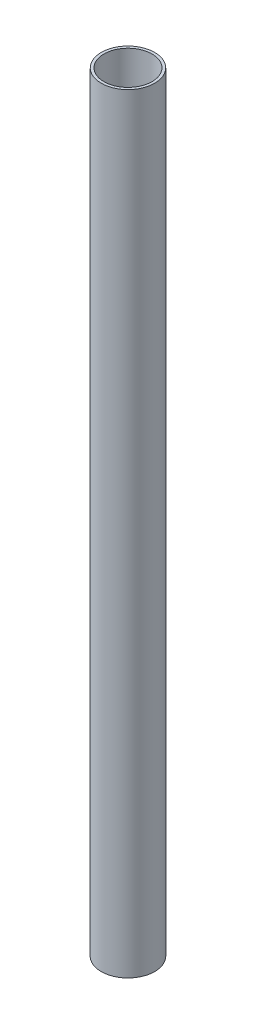
SolidWorks part; units mm, degrees
material "6061-T6 (SS)"
ref_plane "Front Plane" through (0, 0, 0) normal (0, 0, 1) x (1, 0, 0)
ref_plane "Top Plane" through (0, 0, 0) normal (0, 1, 0) x (1, 0, 0)
ref_plane "Right Plane" through (0, 0, 0) normal (1, 0, 0) x (0, 0, -1)
sketch "Sketch1" plane through (0, 0, 0) normal (0, 1, 0) x (1, 0, 0)
  circle A0 centre (0, 0) radius 31.75
  dimension "D1" = 63.5
extrude "Boss-Extrude1" add sketch "Sketch1" against normal blind 914.4
sketch "Sketch2" plane through (0, 0, 0) normal (0, 1, 0) x (1, 0, 0)
  circle A0 centre (0, 0) radius 28.575
  dimension "D1" = 57.15
extrude "Cut-Extrude1" cut sketch "Sketch2" against normal through all
